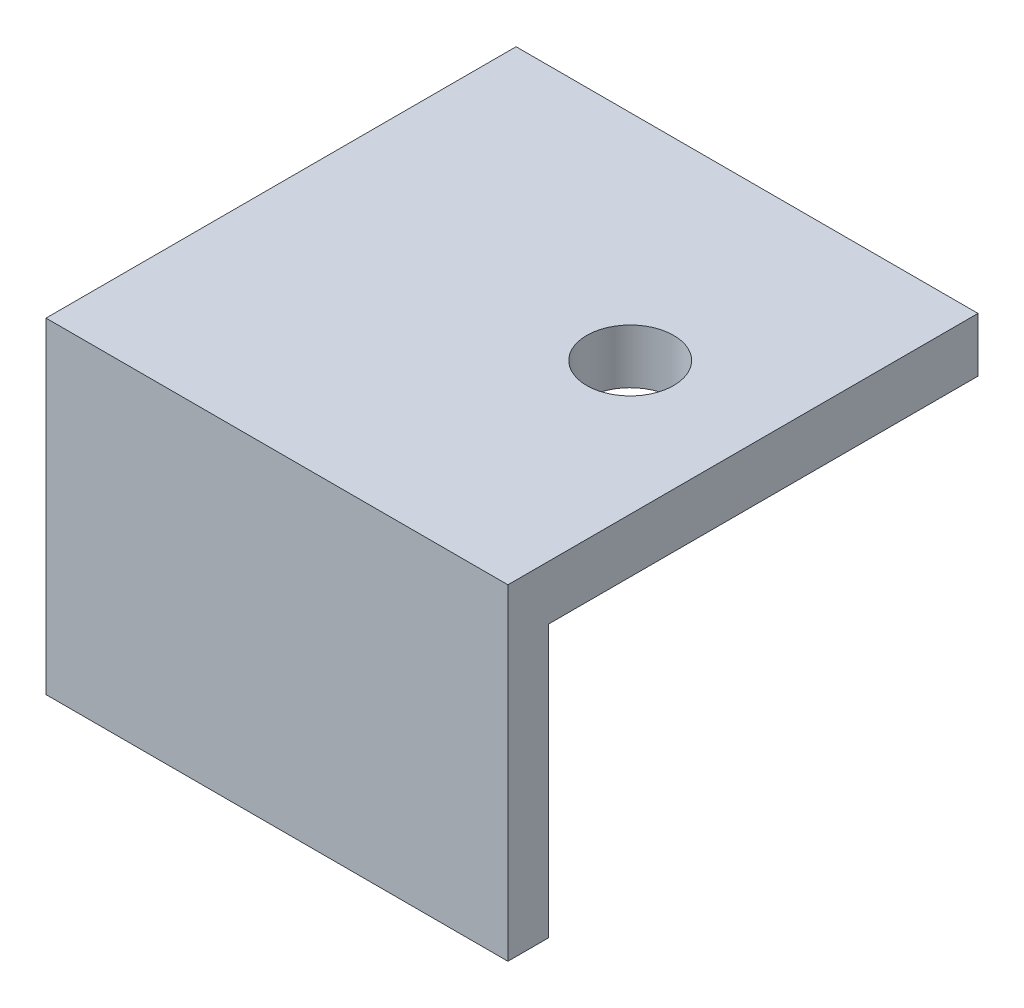
SolidWorks part; units mm, degrees
ref_plane "前视基准面" through (0, 0, 0) normal (0, 0, 1) x (1, 0, 0)
ref_plane "上视基准面" through (0, 0, 0) normal (0, 1, 0) x (1, 0, 0)
ref_plane "右视基准面" through (0, 0, 0) normal (1, 0, 0) x (0, 0, -1)
sketch "草图1" plane through (0, 0, 0) normal (0, 1, 0) x (1, 0, 0)
  line L0 (1.5, 1.5) -> (1.5, 17.3)
  line L1 (0, 0) -> (17, 0)
  line L2 (0, 0) -> (0, 18.8)
  line L3 (0, 18.8) -> (17, 18.8)
  line L4 (17, 0) -> (17, 1.5)
  line L5 (1.5, 17.3) -> (15.5, 17.3)
  line L7 (1.5, 1.5) -> (15.5, 1.5)
  line L8 (15.5, 17.3) -> (17, 17.3)
  line L9 (15.5, 1.5) -> (17, 1.5)
  line L10 (17, 17.3) -> (17, 18.8)
  line L11 (17, 0) -> (17, 18.8) construction
  line L12 (15.5, 1.5) -> (15.5, 17.3) construction
  dimension "D2" = 15.8
  dimension "D3" = 17
  dimension "D1" = 1.5
extrude "凸台-拉伸1" add sketch "草图1" along normal blind 10
sketch "草图2" plane through (0, 10, 0) normal (0, 1, 0) x (1, 0, 0)
  line L0 (17, 18.8) -> (0, 18.8) construction
  line L1 (0, 0) -> (17, 0)
  line L2 (0, 0) -> (0, 18.8)
  line L3 (0, 18.8) -> (17, 18.8)
  line L4 (17, 0) -> (17, 18.8)
  line L5 (0, 9.4) -> (20.1724, 9.4) construction
  line L6 (1.5, 1.5) -> (1.5, 17.3) construction
  circle A0 centre (12.1, 9.4) radius 1.6
  dimension "D1" = 10.6
  dimension "D2" = 3.2
extrude "凸台-拉伸2" add sketch "草图2" along normal blind 2
sketch "草图4" plane through (0, 0, 0) normal (0, -1, 0) x (1, 0, 0)
  line L1 (17, -17.3) -> (0, -17.3)
  line L2 (17, -17.3) -> (17, -18.8)
  line L3 (17, -18.8) -> (0, -18.8)
  line L4 (0, -17.3) -> (0, -18.8)
extrude "切除-拉伸1" cut sketch "草图4" against normal through all
